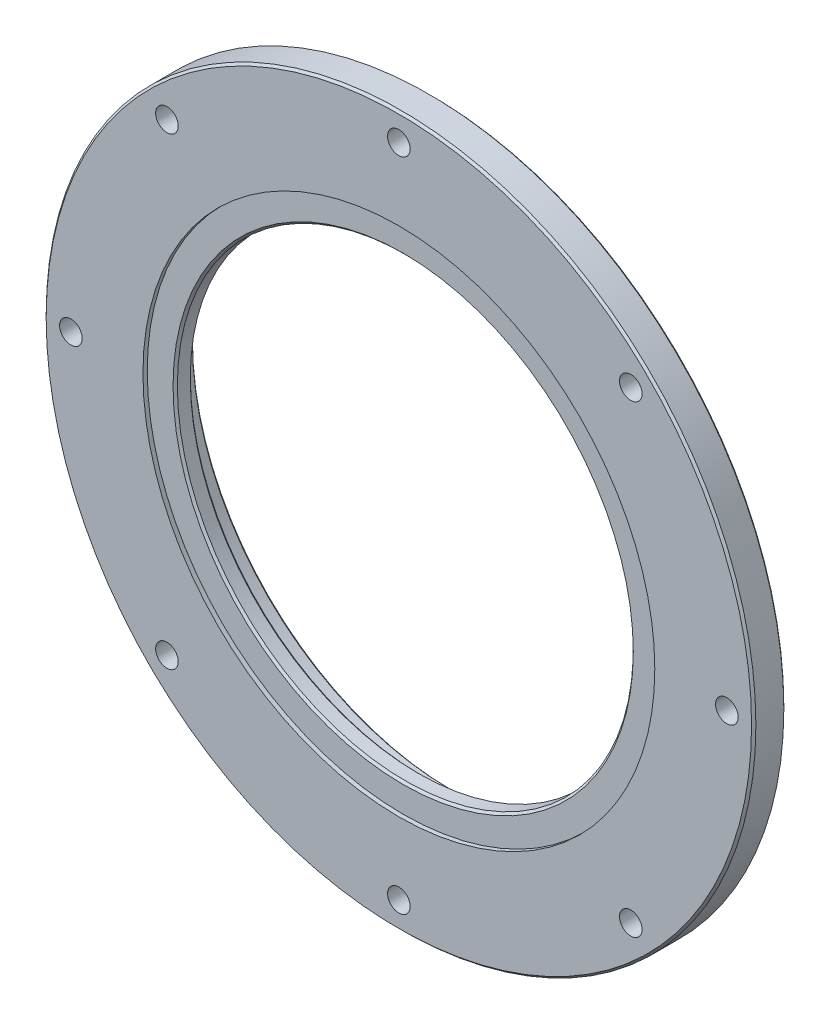
SolidWorks part; units mm, degrees
ref_plane "Front Plane" through (0, 0, 0) normal (0, 0, 1) x (1, 0, 0)
ref_plane "Top Plane" through (0, 0, 0) normal (0, 1, 0) x (1, 0, 0)
ref_plane "Right Plane" through (0, 0, 0) normal (1, 0, 0) x (0, 0, -1)
ref_plane "Plane1" through (0, 0, 0) normal (0, -1, 0) x (1, 0, 0)
sketch "Sketch1" plane through (0, 0, 0) normal (0, -1, 0) x (1, 0, 0)
  line L0 (165, 0) -> (0, 0)
  line L1 (0, 0) -> (0, -15)
  line L2 (0, -15) -> (165, -15)
  line L3 (165, -15) -> (165, 0)
  line L4 (0, 0) -> (0, -15) construction
revolve "Revolve1" add sketch "Sketch1" angle 360 about L4
sketch "Sketch2" plane through (0, 0, -15) normal (0, 0, -1) x (-1, 0, 0)
  circle A0 centre (0, 0) radius 140
extrude "Boss-Extrude1" add sketch "Sketch2" along normal blind 10
sketch "Sketch3" plane through (0, 0, 0) normal (0, -1, 0) x (1, 0, 0)
  line L0 (119, 0) -> (0, 0)
  line L1 (0, 0) -> (0, -25)
  line L2 (0, -25) -> (120, -25)
  line L3 (120, -25) -> (120, -10)
  line L4 (120, -10) -> (106, -10)
  line L5 (106, -10) -> (106, -2)
  line L6 (106, -2) -> (119, -2)
  line L7 (119, -2) -> (119, 0)
  line L8 (0, 0) -> (0, -25) construction
  line L9 (0, 27.169) -> (0, -45.3182) construction
  line L10 (165, 0) -> (-165, 0) construction
  dimension "D1" = 106
  dimension "D2" = 119
  dimension "D3" = 120
  dimension "D4" = 15
  dimension "D5" = 25
  dimension "D6" = 2
revolve "Cut-Revolve1" cut sketch "Sketch3" angle 360 about L8
ref_plane "Plane2" through (0, -49.7488, 0) normal (0, 1, 0) x (1, 0, 0)
sketch "Sketch4" plane through (0, -49.7488, 0) normal (0, 1, 0) x (1, 0, 0)
  line L0 (-116.7808, 25) -> (-120.1043, 25)
  line L1 (-120.1043, 25) -> (-120.1043, 10)
  line L2 (-120.1043, 10) -> (-116.7808, 11.997)
  line L3 (-116.7808, 11.997) -> (-116.7808, 15)
  line L4 (-116.7808, 15) -> (-116.7808, 25)
  line L5 (-120.1043, 25) -> (-120.1043, 10) construction
revolve "Cut-Revolve2" cut sketch "Sketch4" angle 360 about L5
ref_plane "Plane3" through (0, -120.1043, 0) normal (0, 1, 0) x (1, 0, 0)
sketch "Sketch5" plane through (0, -120.1043, 0) normal (0, 1, 0) x (1, 0, 0)
  line L0 (-46.4253, 25) -> (-49.7488, 25)
  line L1 (-49.7488, 25) -> (-49.7488, 10)
  line L2 (-49.7488, 10) -> (-46.4253, 11.997)
  line L3 (-46.4253, 11.997) -> (-46.4253, 15)
  line L4 (-46.4253, 15) -> (-46.4253, 25)
  line L5 (-49.7488, 25) -> (-49.7488, 10) construction
revolve "Cut-Revolve3" cut sketch "Sketch5" angle 360 about L5
sketch "Sketch6" plane through (0, -120.1043, 0) normal (0, 1, 0) x (1, 0, 0)
  line L0 (53.0723, 25) -> (49.7488, 25)
  line L1 (49.7488, 25) -> (49.7488, 10)
  line L2 (49.7488, 10) -> (53.0723, 11.997)
  line L3 (53.0723, 11.997) -> (53.0723, 15)
  line L4 (53.0723, 15) -> (53.0723, 25)
  line L5 (49.7488, 25) -> (49.7488, 10) construction
revolve "Cut-Revolve4" cut sketch "Sketch6" angle 360 about L5
sketch "Sketch7" plane through (0, -49.7488, 0) normal (0, 1, 0) x (1, 0, 0)
  line L0 (123.4278, 25) -> (120.1043, 25)
  line L1 (120.1043, 25) -> (120.1043, 10)
  line L2 (120.1043, 10) -> (123.4278, 11.997)
  line L3 (123.4278, 11.997) -> (123.4278, 15)
  line L4 (123.4278, 15) -> (123.4278, 25)
  line L5 (120.1043, 25) -> (120.1043, 10) construction
revolve "Cut-Revolve5" cut sketch "Sketch7" angle 360 about L5
ref_plane "Plane4" through (0, 49.7488, 0) normal (0, 1, 0) x (1, 0, 0)
sketch "Sketch8" plane through (0, 49.7488, 0) normal (0, 1, 0) x (1, 0, 0)
  line L0 (123.4278, 25) -> (120.1043, 25)
  line L1 (120.1043, 25) -> (120.1043, 10)
  line L2 (120.1043, 10) -> (123.4278, 11.997)
  line L3 (123.4278, 11.997) -> (123.4278, 15)
  line L4 (123.4278, 15) -> (123.4278, 25)
  line L5 (120.1043, 25) -> (120.1043, 10) construction
revolve "Cut-Revolve6" cut sketch "Sketch8" angle 360 about L5
ref_plane "Plane5" through (0, 120.1043, 0) normal (0, 1, 0) x (1, 0, 0)
sketch "Sketch9" plane through (0, 120.1043, 0) normal (0, 1, 0) x (1, 0, 0)
  line L0 (53.0723, 25) -> (49.7488, 25)
  line L1 (49.7488, 25) -> (49.7488, 10)
  line L2 (49.7488, 10) -> (53.0723, 11.997)
  line L3 (53.0723, 11.997) -> (53.0723, 15)
  line L4 (53.0723, 15) -> (53.0723, 25)
  line L5 (49.7488, 25) -> (49.7488, 10) construction
revolve "Cut-Revolve7" cut sketch "Sketch9" angle 360 about L5
sketch "Sketch10" plane through (0, 120.1043, 0) normal (0, 1, 0) x (1, 0, 0)
  line L0 (-46.4253, 25) -> (-49.7488, 25)
  line L1 (-49.7488, 25) -> (-49.7488, 10)
  line L2 (-49.7488, 10) -> (-46.4253, 11.997)
  line L3 (-46.4253, 11.997) -> (-46.4253, 15)
  line L4 (-46.4253, 15) -> (-46.4253, 25)
  line L5 (-49.7488, 25) -> (-49.7488, 10) construction
revolve "Cut-Revolve8" cut sketch "Sketch10" angle 360 about L5
sketch "Sketch11" plane through (0, 49.7488, 0) normal (0, 1, 0) x (1, 0, 0)
  line L0 (-116.7808, 25) -> (-120.1043, 25)
  line L1 (-120.1043, 25) -> (-120.1043, 10)
  line L2 (-120.1043, 10) -> (-116.7808, 11.997)
  line L3 (-116.7808, 11.997) -> (-116.7808, 15)
  line L4 (-116.7808, 15) -> (-116.7808, 25)
  line L5 (-120.1043, 25) -> (-120.1043, 10) construction
revolve "Cut-Revolve9" cut sketch "Sketch11" angle 360 about L5
hole_wizard "Ø10.5 (10.5) Diameter Hole1" positions "Sketch13" profile "Sketch12" hole size "Ø10.5" standard "ANSI Metric"
sketch "Sketch13" plane through (0, 0, -15) normal (0, 0, -1) x (-1, 0, 0)
  point P0 (152.5, 0)
  point P1 (107.8338, -107.8338)
  point P2 (0, -152.5)
  point P3 (-107.8338, -107.8338)
  point P4 (-152.5, 0)
  point P5 (-107.8338, 107.8338)
  point P6 (0, 152.5)
  point P7 (107.8338, 107.8338)
sketch "Sketch12" plane through (-152.5, 0, -15) normal (1, 0, 0) x (0, 1, 0)
  line L0 (0, 0) -> (0, 15)
  line L1 (0, 15) -> (5.25, 15)
  line L2 (5.25, 15) -> (5.25, 0)
  line L5 (5.25, 0) -> (0, 0)
  line L11 (0, -6.35) -> (0, 107.95) construction
  dimension "Thru Hole Dia." = 10.5
  dimension "Thru Hole Depth" = 15
chamfer "Chamfer1" distance 1 angle 45 6 edges at (-106, 0, -2) (-106, 0, -10) (-120, 0, -25) (-140, 0, -25) (-165, 0, -15) (-165, 0, 0)
